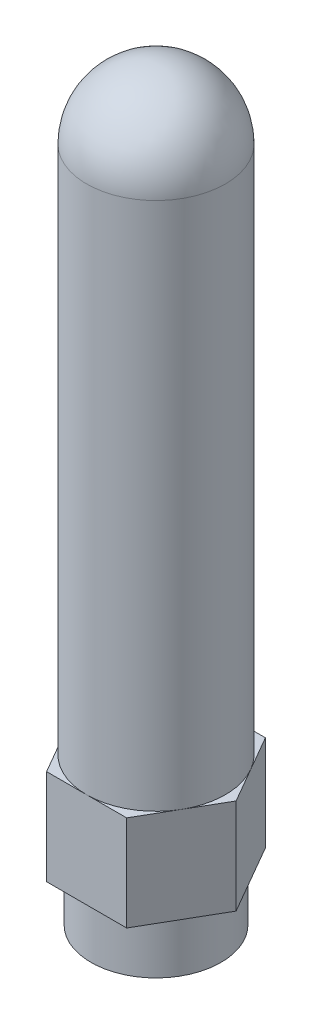
SolidWorks part; units mm, degrees
ref_plane "Front Plane" through (0, 0, 0) normal (0, 0, 1) x (1, 0, 0)
ref_plane "Top Plane" through (0, 0, 0) normal (0, 1, 0) x (1, 0, 0)
ref_plane "Right Plane" through (0, 0, 0) normal (1, 0, 0) x (0, 0, -1)
sketch "Sketch1" plane through (0, 0, 0) normal (0, 0, 1) x (1, 0, 0)
  line L0 (0, 0) -> (4, 0)
  line L1 (4, 0) -> (4, 36)
  line L2 (0, 0) -> (0, 40)
  arc A0 (0, 40) -> (4, 36) centre (0, 36) cw
  point P6 (0, 0)
  dimension "D1" = 4
  dimension "D2" = 40
revolve "Revolve1" add sketch "Sketch1" angle 360 about L2
sketch "Sketch2" plane through (0, 0, 0) normal (0, 1, 0) x (1, 0, 0)
  line L1 (4.6188, 0) -> (2.3094, 4)
  line L2 (2.3094, 4) -> (-2.3094, 4)
  line L3 (-2.3094, 4) -> (-4.6188, 0)
  line L4 (-4.6188, 0) -> (-2.3094, -4)
  line L5 (-2.3094, -4) -> (2.3094, -4)
  line L6 (2.3094, -4) -> (4.6188, 0)
  circle A0 centre (0, 0) radius 4 construction
  point P1 (0, 0)
  dimension "D1" = 8
extrude "Boss-Extrude1" add sketch "Sketch2" along normal blind 5.5
sketch "Sketch3" plane through (0, 0, 0) normal (0, -1, 0) x (1, 0, 0)
  circle A0 centre (0, 0) radius 3.75
  dimension "D1" = 7.5
extrude "Boss-Extrude2" add sketch "Sketch3" along normal blind 3
sketch "Sketch4" plane through (0, -3, 0) normal (0, -1, 0) x (1, 0, 0)
  circle A0 centre (0, 0) radius 3
  dimension "D1" = 6
extrude "Cut-Extrude1" cut sketch "Sketch4" against normal blind 8
